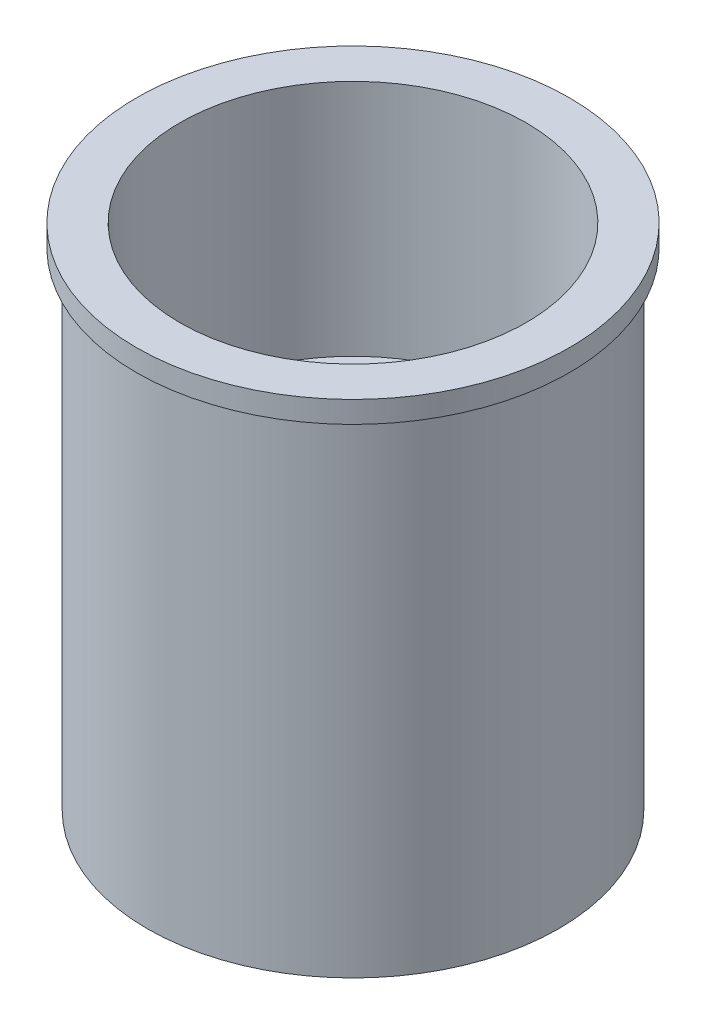
SolidWorks part; units mm, degrees
ref_plane "Plan de face" through (0, 0, 0) normal (0, 0, 1) x (1, 0, 0)
ref_plane "Plan de dessus" through (0, 0, 0) normal (0, 1, 0) x (1, 0, 0)
ref_plane "Plan de droite" through (0, 0, 0) normal (1, 0, 0) x (0, 0, -1)
sketch "Esquisse1" plane through (0, 0, 0) normal (0, 0, 1) x (1, 0, 0)
  line L0 (0, 35.1892) -> (0, -43.6216) construction
  line L1 (-16, -15.1622) -> (-16, 6.8378)
  line L2 (-16, 6.8378) -> (-14, 6.8378)
  line L3 (-14, 6.8378) -> (-14, 9.8378)
  line L4 (-14, 9.8378) -> (-16, 9.8378)
  line L5 (-16, 9.8378) -> (-16, 31.8378)
  line L6 (-16, 31.8378) -> (-20, 31.8378)
  line L7 (-20, 31.8378) -> (-20, 29.8378)
  line L8 (-20, 29.8378) -> (-19, 29.8378)
  line L9 (-19, 29.8378) -> (-19, -15.1622)
  line L10 (-19, -15.1622) -> (-16, -15.1622)
  point P5 (-18, 31.8378)
  dimension "D1" = 3
  dimension "D2" = 22
  dimension "D3" = 3
  dimension "D4" = 4
  dimension "D5" = 2
  dimension "D6" = 3
  dimension "D7" = 2
  dimension "D8" = 16
  dimension "D9" = 47
revolve "Révolution1" add sketch "Esquisse1" angle 360 about L0
